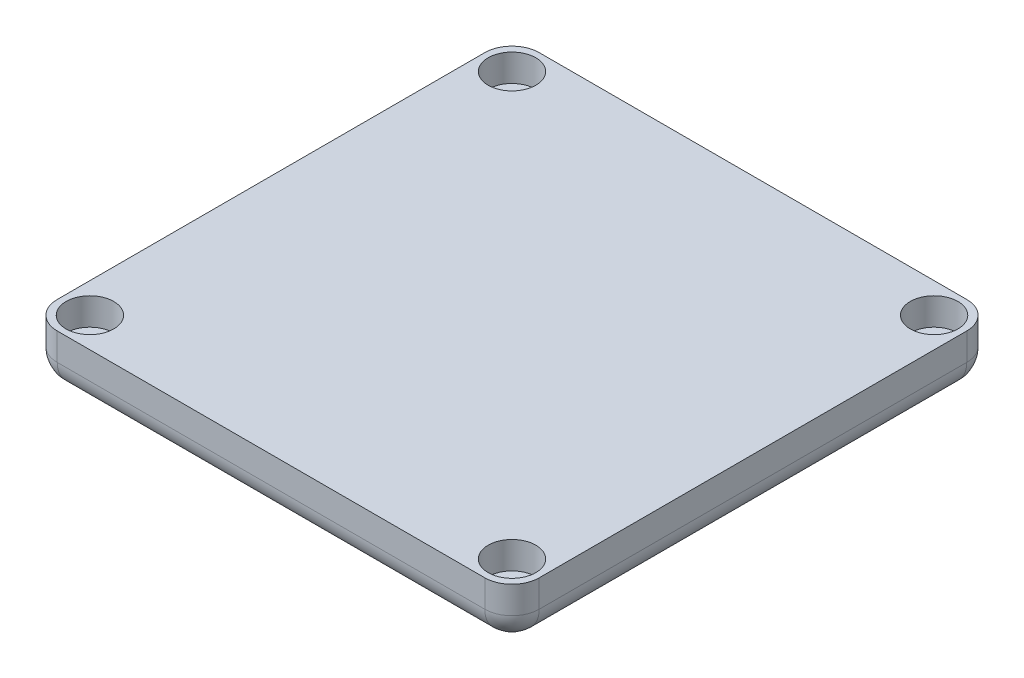
SolidWorks part; units mm, degrees
ref_plane "Plan de face" through (0, 0, 0) normal (0, 0, 1) x (1, 0, 0)
ref_plane "Plan de dessus" through (0, 0, 0) normal (0, 1, 0) x (1, 0, 0)
ref_plane "Plan de droite" through (0, 0, 0) normal (1, 0, 0) x (0, 0, -1)
sketch "Esquisse1" plane through (0, 0, 0) normal (0, 1, 0) x (1, 0, 0)
  line L1 (-17.7, -17.7) -> (17.7, -17.7)
  line L2 (-17.7, -17.7) -> (-17.7, 17.7)
  line L3 (-17.7, 17.7) -> (17.7, 17.7)
  line L4 (17.7, -17.7) -> (17.7, 17.7)
  line L5 (-17.7, -17.7) -> (17.7, 17.7) construction
  line L6 (-17.7, 17.7) -> (17.7, -17.7) construction
  point P0 (0, 0)
  dimension "D1" = 35.4
  dimension "D2" = 35.4
extrude "Boss.-Extru.1" add sketch "Esquisse1" along normal blind 4
fillet "Congé1" radius 2 8 edges at (-17.7, 2, -17.7) (0, 0, -17.7) (17.7, 2, -17.7) (17.7, 0, 0) (17.7, 2, 17.7) (0, 0, 17.7) (-17.7, 0, 0) (-17.7, 2, 17.7)
sketch "Esquisse2" plane through (0, 4, 0) normal (0, 1, 0) x (1, 0, 0)
  line L0 (17.7, -15.7) -> (17.7, 15.7) construction
  line L1 (15.7, 17.7) -> (-15.7, 17.7) construction
  line L2 (-17.7, 15.7) -> (-17.7, -15.7) construction
  line L3 (-15.7, -17.7) -> (15.7, -17.7) construction
  circle A0 centre (-15.5, 15.5) radius 1.75
  circle A1 centre (15.5, 15.5) radius 1.75
  circle A2 centre (15.5, -15.5) radius 1.75
  circle A3 centre (-15.5, -15.5) radius 1.75
  dimension "D1" = 3.5
  dimension "D2" = 3.5
  dimension "D3" = 3.5
  dimension "D4" = 3.5
  dimension "D5" = 2.2
  dimension "D6" = 2.2
  dimension "D7" = 2.2
  dimension "D8" = 2.2
  dimension "D9" = 2.2
  dimension "D10" = 2.2
  dimension "D11" = 2.2
  dimension "D12" = 2.2
extrude "Enlèv. mat.-Extru.1" cut sketch "Esquisse2" against normal blind 2
sketch "Esquisse3" plane through (0, 4, 0) normal (0, 1, 0) x (1, 0, 0)
  line L1 (-12.25, 12.25) -> (12.25, 12.25)
  line L2 (-12.25, 12.25) -> (-12.25, -12.25)
  line L3 (-12.25, -12.25) -> (12.25, -12.25)
  line L4 (12.25, 12.25) -> (12.25, -12.25)
  line L5 (-12.25, 12.25) -> (12.25, -12.25) construction
  line L6 (-12.25, -12.25) -> (12.25, 12.25) construction
  point P0 (0, 0)
  dimension "D1" = 24.5
  dimension "D2" = 24.5
